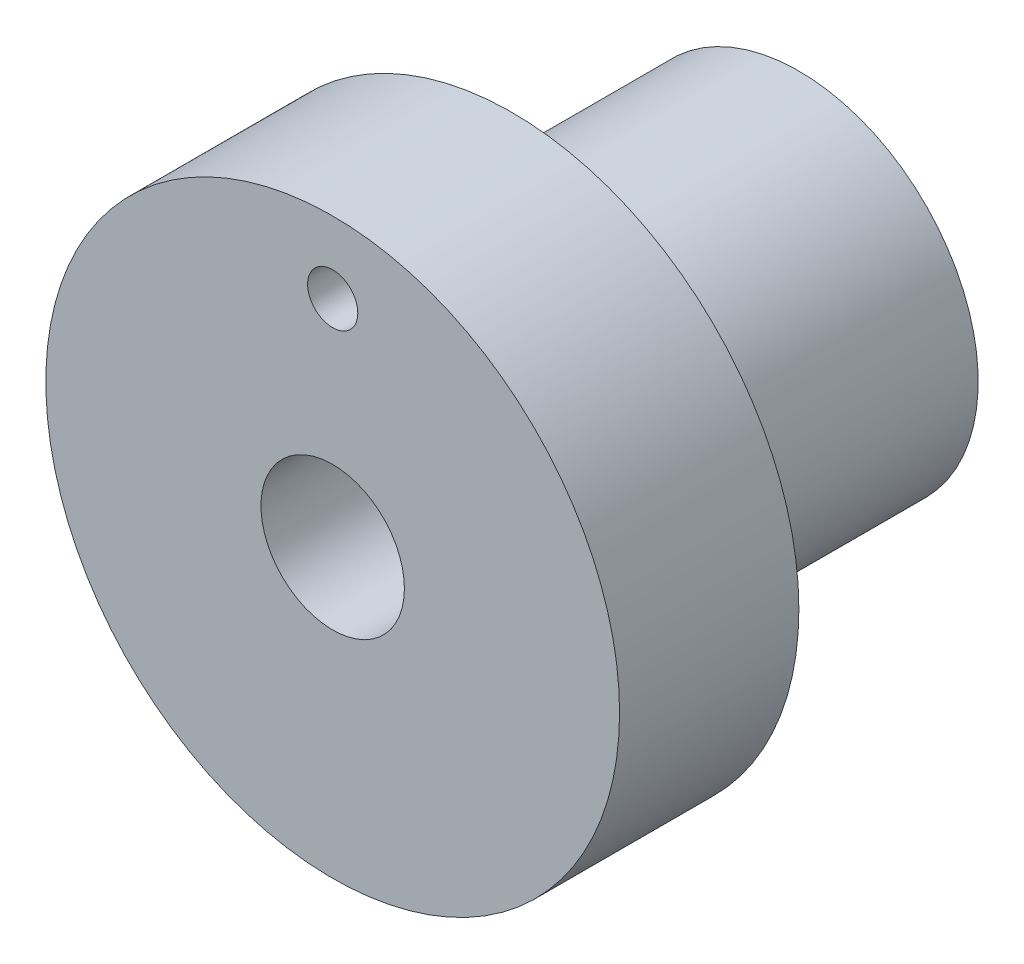
SolidWorks part; units mm, degrees
material "POLYURETHANE (11671)"
ref_plane "Front Plane" through (0, 0, 0) normal (0, 0, 1) x (1, 0, 0)
ref_plane "Top Plane" through (0, 0, 0) normal (0, 1, 0) x (1, 0, 0)
ref_plane "Right Plane" through (0, 0, 0) normal (1, 0, 0) x (0, 0, -1)
sketch "Sketch2" plane through (0, 0, 0) normal (0, 0, 1) x (1, 0, 0)
  circle A0 centre (0, 0) radius 40
  dimension "D1" = 80
extrude "Boss-Extrude1" add sketch "Sketch2" against normal blind 25
sketch "Sketch3" plane through (0, 0, -25) normal (0, 0, -1) x (-1, 0, 0)
  circle A0 centre (0, 0) radius 25
  dimension "D1" = 50
extrude "Boss-Extrude2" add sketch "Sketch3" along normal blind 40 contours A0
sketch "Sketch4" plane through (0, 0, 0) normal (0, 0, 1) x (1, 0, 0)
  circle A0 centre (0, 0) radius 10
  dimension "D1" = 20
extrude "Cut-Extrude1" cut sketch "Sketch4" against normal through all
cosmetic thread "Cosmetic Thread1" parameters "D2"=21
sketch "Sketch5" plane through (0, 0, 0) normal (0, 0, 1) x (1, 0, 0)
  circle A0 centre (0, 30) radius 3.5
  circle A1 centre (0, 0) radius 40 construction
  dimension "D1" = 7
  dimension "D2" = 30
extrude "Cut-Extrude2" cut sketch "Sketch5" against normal through all
cosmetic thread "Cosmetic Thread2" parameters "D2"=8
